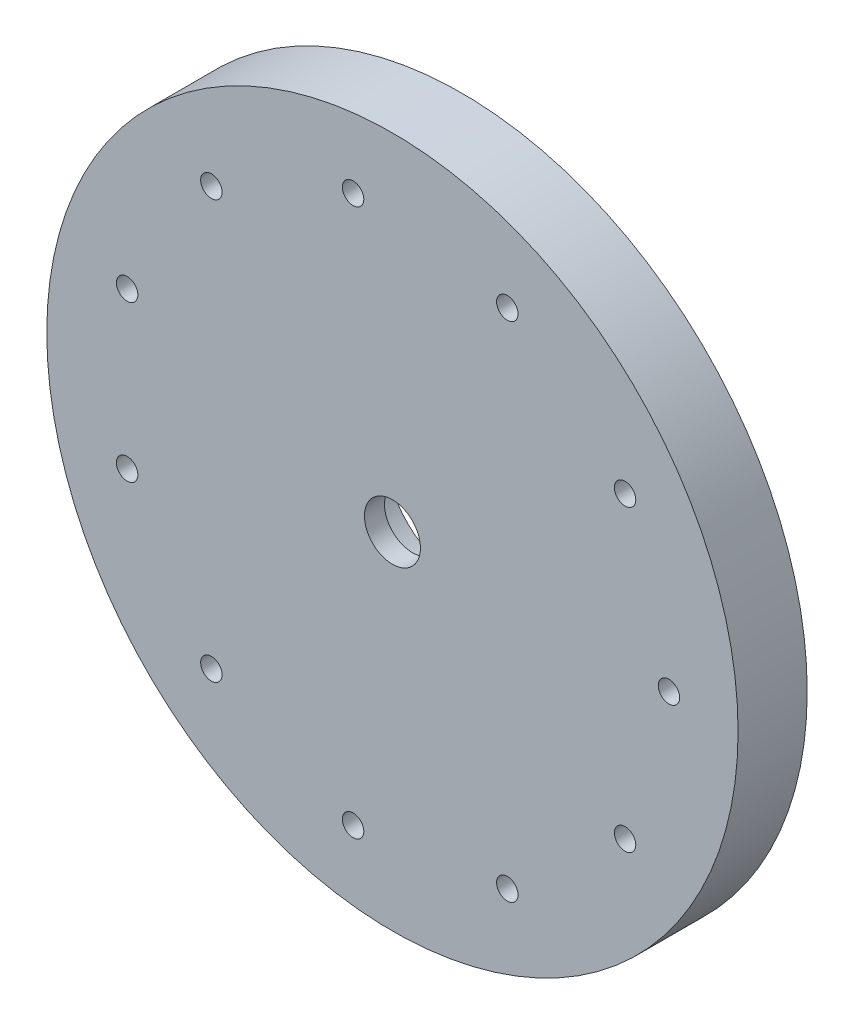
SolidWorks part; units mm, degrees
ref_plane "Front Plane" through (0, 0, 0) normal (0, 0, 1) x (1, 0, 0)
ref_plane "Top Plane" through (0, 0, 0) normal (0, 1, 0) x (1, 0, 0)
ref_plane "Right Plane" through (0, 0, 0) normal (1, 0, 0) x (0, 0, -1)
sketch "Sketch1" plane through (0, 0, 0) normal (0, 0, 1) x (1, 0, 0)
  circle A0 centre (0, 0) radius 50
  circle A1 centre (0, 0) radius 11.05
  circle A2 centre (0, 0) radius 40 construction
  circle A3 centre (40, 0) radius 1.55
  circle A4 centre (33.6501, -21.6256) radius 1.55
  circle A5 centre (16.6166, -36.3853) radius 1.55
  circle A6 centre (-5.6926, -39.5929) radius 1.55
  circle A7 centre (-26.1944, -30.23) radius 1.55
  circle A8 centre (-38.3797, -11.2693) radius 1.55
  circle A9 centre (-38.3797, 11.2693) radius 1.55
  circle A10 centre (-26.1944, 30.23) radius 1.55
  circle A11 centre (-5.6926, 39.5929) radius 1.55
  circle A12 centre (16.6166, 36.3853) radius 1.55
  circle A13 centre (33.6501, 21.6256) radius 1.55
  point P31 (0, 0)
  dimension "D1" = 22.1
  dimension "D2" = 100
  dimension "D3" = 80
  dimension "D4" = 3.1
extrude "Boss-Extrude1" add sketch "Sketch1" along normal blind 10
sketch "Sketch2" plane through (0, 0, 10) normal (0, 0, 1) x (1, 0, 0)
  circle A0 centre (0, 0) radius 4.05
  circle A1 centre (0, 0) radius 11.05 construction
  circle A2 centre (0, 0) radius 11.05
  dimension "D1" = 8.1
extrude "Boss-Extrude2" add sketch "Sketch2" against normal blind 2.9
